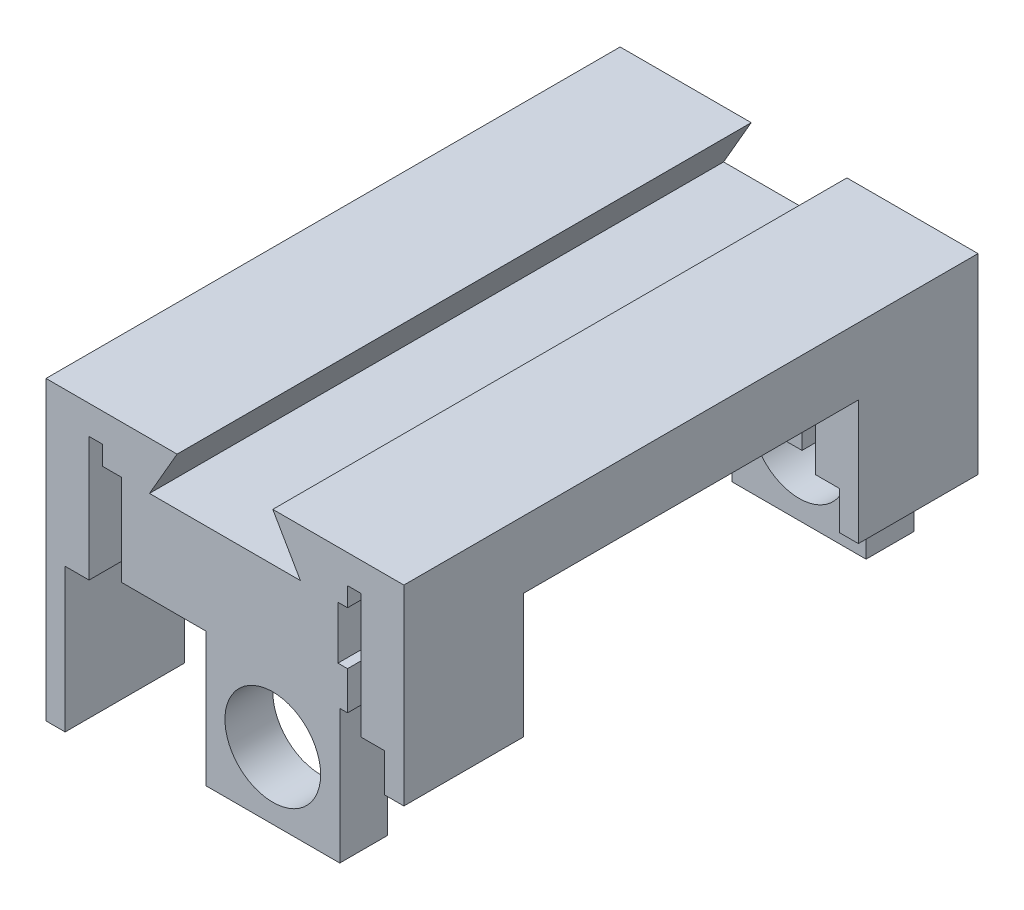
SolidWorks part; units mm, degrees
ref_plane "Front Plane" through (0, 0, 0) normal (0, 0, 1) x (1, 0, 0)
ref_plane "Top Plane" through (0, 0, 0) normal (0, 1, 0) x (1, 0, 0)
ref_plane "Right Plane" through (0, 0, 0) normal (1, 0, 0) x (0, 0, -1)
sketch "Sketch1" plane through (0, 0, 0) normal (0, 0, 1) x (1, 0, 0)
  line L0 (-16.27, 6.97) -> (16.27, 6.97)
  line L3 (21.209, 5.08) -> (21.209, 0)
  line L4 (21.209, 0) -> (23.749, 0)
  line L5 (23.749, 0) -> (23.749, 25.4)
  line L10 (23.749, 25.4) -> (-23.749, 25.4)
  line L11 (-23.749, 25.4) -> (-23.749, 0)
  line L12 (-23.749, 0) -> (-21.209, 0)
  line L13 (-21.209, 0) -> (-21.209, 5.08)
  line L16 (-16.27, 6.97) -> (-16.27, 12.05)
  line L17 (-16.27, 12.05) -> (-15, 12.05)
  line L18 (-15, 12.05) -> (-15, 19.05)
  line L19 (-15, 19.05) -> (-16.27, 19.05)
  line L20 (-16.27, 19.05) -> (-16.27, 21.59)
  line L21 (16.27, 21.59) -> (16.27, 19.05)
  line L22 (16.27, 19.05) -> (15, 19.05)
  line L23 (15, 19.05) -> (15, 12.05)
  line L24 (15, 12.05) -> (16.27, 12.05)
  line L25 (16.27, 12.05) -> (16.27, 6.97)
  line L26 (-16.27, 21.59) -> (-18.034, 21.59)
  line L27 (-18.034, 21.59) -> (-18.034, 5.08)
  line L28 (-18.034, 5.08) -> (-21.209, 5.08)
  line L29 (16.27, 21.59) -> (18.034, 21.59)
  line L30 (18.034, 21.59) -> (18.034, 5.08)
  line L31 (18.034, 5.08) -> (21.209, 5.08)
  line L32 (0, 0) -> (0, 6.97) construction
  dimension "D1" = 30
  dimension "D2" = 7
  dimension "D3" = 1.27
  dimension "D4" = 42.418
  dimension "D5" = 2.54
  dimension "D9" = 25.4
  dimension "D10" = 2.54
  dimension "D11" = 5.08
  dimension "D12" = 3.175
  dimension "D13" = 3.81
  dimension "D14" = 5.08
extrude "Boss-Extrude1" add sketch "Sketch1" along normal blind 76.2
sketch "Sketch2" plane through (0, 0, 76.2) normal (0, 0, 1) x (1, 0, 0)
  line L0 (-21.209, 5.08) -> (-23.749, 5.08)
  line L1 (-23.749, 25.4) -> (-23.749, 0) construction
  line L2 (-23.749, 5.08) -> (-23.749, -13.97)
  line L3 (-23.749, -13.97) -> (-21.209, -13.97)
  line L4 (-21.209, -13.97) -> (-21.209, 5.08)
  line L5 (-21.209, 5.08) -> (-18.034, 5.08) construction
  dimension "D1" = 19.05
extrude "Boss-Extrude2" add sketch "Sketch2" against normal up to surface (76.2 mm away) up to face at (0, 12.3258, 0)
sketch "Sketch3" plane through (0, 0, 76.2) normal (0, 0, 1) x (1, 0, 0)
  line L0 (-2.54, 6.97) -> (15.24, 6.97)
  line L2 (15.24, 6.97) -> (15.24, -10.81)
  line L3 (15.24, -10.81) -> (-2.54, -10.81)
  line L4 (-2.54, -10.81) -> (-2.54, 6.97)
  line L6 (-2.54, 6.97) -> (15.24, -10.81) construction
  line L7 (-16.27, 6.97) -> (16.27, 6.97) construction
  circle A0 centre (6.35, -1.92) radius 6.35
  dimension "D2" = 12.7
  dimension "D1" = 2.54
  dimension "D3" = 6.35
extrude "Boss-Extrude3" add sketch "Sketch3" against normal blind 6.35
ref_plane "Plane1" through (0, 0, 38.1) normal (0, 0, 1) x (1, 0, 0)
mirror "Mirror1" about plane through (0, 0, 38.1) normal (0, 0, 1) of "Boss-Extrude3"
sketch "Sketch4" plane through (0, 0, 76.2) normal (0, 0, 1) x (1, 0, 0)
  line L0 (-6.35, 25.4) -> (-10.0162, 19.05)
  line L1 (23.749, 25.4) -> (-23.749, 25.4) construction
  line L2 (-10.0162, 19.05) -> (10.0162, 19.05)
  line L3 (10.0162, 19.05) -> (6.35, 25.4)
  line L4 (6.35, 25.4) -> (-6.35, 25.4)
  point P5 (0, 25.4)
  dimension "D1" = 60
  dimension "D2" = 12.7
  dimension "D3" = 6.35
extrude "Cut-Extrude1" cut sketch "Sketch4" against normal through all
sketch "Sketch5" plane through (23.749, 0, 0) normal (1, 0, 0) x (0, 0, -1)
  line L0 (0, -13.97) -> (-76.2, -13.97) construction
  line L1 (-60.325, -13.97) -> (-15.875, -13.97)
  line L2 (-60.325, -13.97) -> (-60.325, 16.51)
  line L3 (-60.325, 16.51) -> (-15.875, 16.51)
  line L4 (-15.875, -13.97) -> (-15.875, 16.51)
  point P6 (-38.1, -13.97)
  dimension "D1" = 44.45
  dimension "D2" = 30.48
extrude "Cut-Extrude2" cut sketch "Sketch5" against normal through all
sketch "Sketch6" plane through (0, 0, 76.2) normal (0, 0, 1) x (1, 0, 0)
  line L0 (-16.27, 6.97) -> (-2.54, 6.97) construction
  line L1 (-16.27, 19.05) -> (-13.73, 19.05)
  line L2 (-16.27, 19.05) -> (-16.27, 6.97)
  line L3 (-16.27, 6.97) -> (-13.73, 6.97)
  line L4 (-13.73, 19.05) -> (-13.73, 6.97)
  dimension "D1" = 2.54
extrude "Cut-Extrude3" cut sketch "Sketch6" against normal up to surface (76.2 mm away)
